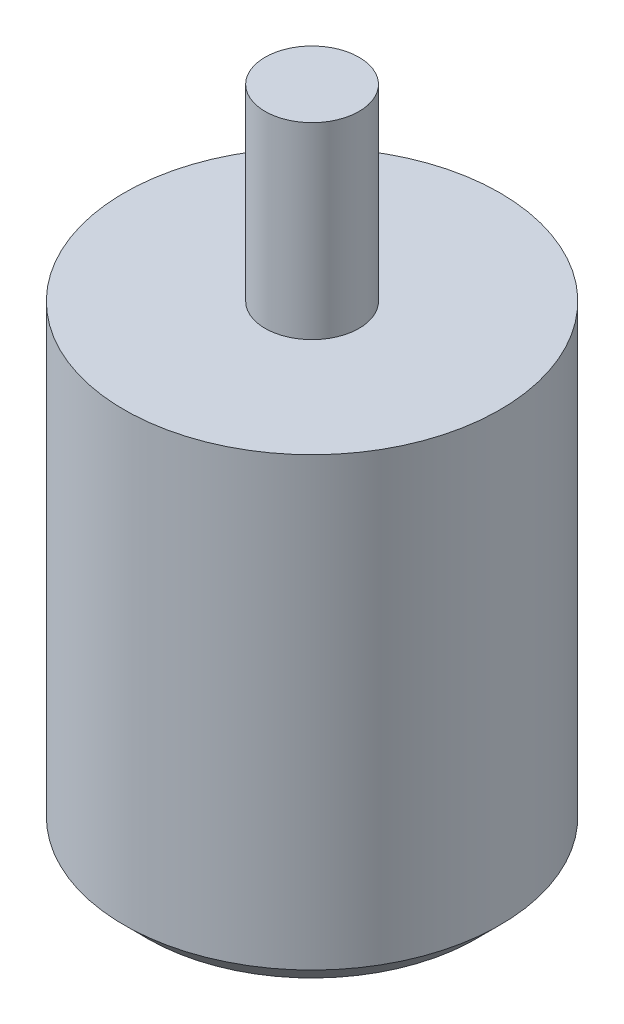
SolidWorks part; units mm, degrees
ref_plane "Front Plane" through (0, 0, 0) normal (0, 0, 1) x (1, 0, 0)
ref_plane "Top Plane" through (0, 0, 0) normal (0, 1, 0) x (1, 0, 0)
ref_plane "Right Plane" through (0, 0, 0) normal (1, 0, 0) x (0, 0, -1)
sketch "Sketch1" plane through (0, 0, 0) normal (0, 0, 1) x (1, 0, 0)
  line L0 (0, 0) -> (0, 32.5664) construction
  line L1 (0, 0) -> (0, 44.45)
  line L2 (0, 44.45) -> (3.175, 44.45)
  line L3 (3.175, 44.45) -> (3.175, 31.75)
  line L4 (3.175, 31.75) -> (12.7, 31.75)
  line L5 (12.7, 31.75) -> (12.7, 0)
  line L6 (12.7, 0) -> (0, 0)
  dimension "D1" = 6.35
  dimension "D2" = 25.4
  dimension "D3" = 12.7
  dimension "D4" = 31.75
revolve "Revolve1" add sketch "Sketch1" angle 360 about L0
chamfer "Chamfer1" distance 1.5875 angle 45 1 edges at (0, 0, -12.7)
